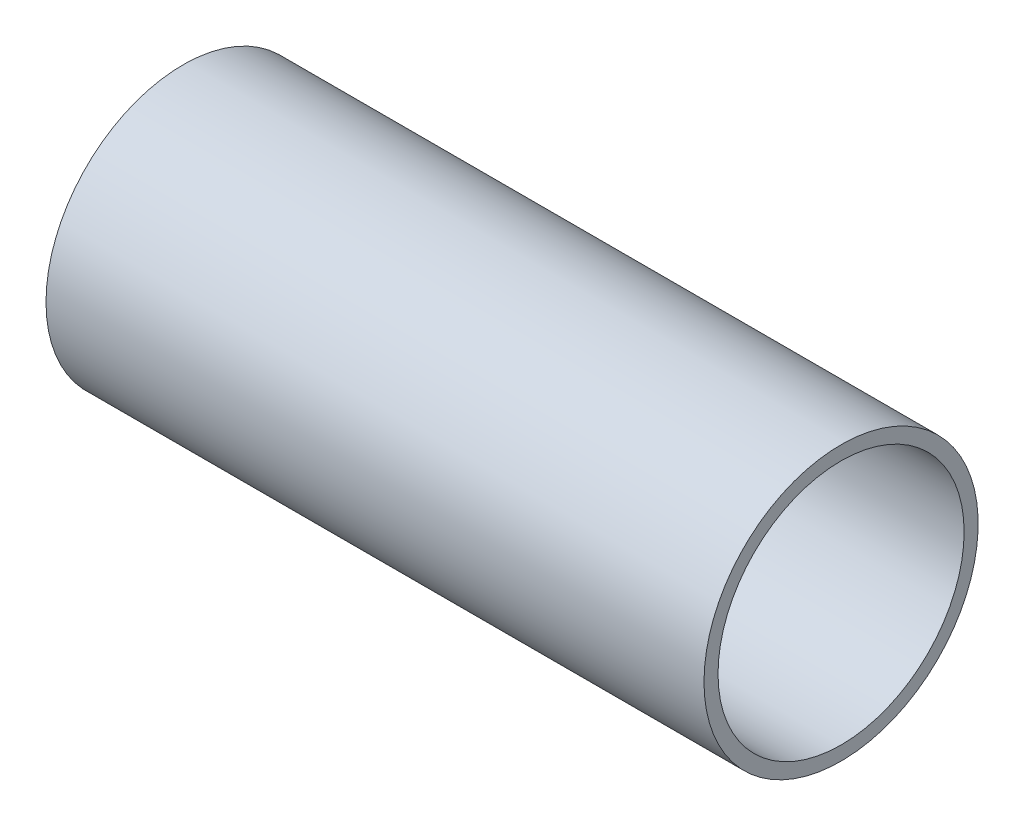
SolidWorks part; units mm, degrees
ref_plane "Front" through (0, 0, 0) normal (0, 0, 1) x (1, 0, 0)
ref_plane "Top" through (0, 0, 0) normal (0, 1, 0) x (1, 0, 0)
ref_plane "Right" through (0, 0, 0) normal (1, 0, 0) x (0, 0, -1)
sketch "Sketch1" plane through (0, 0, 0) normal (1, 0, 0) x (0, 0, -1)
  circle A0 centre (0, 0) radius 14.25
  circle A1 centre (0, 0) radius 15.875
  dimension "D1" = 28.5
  dimension "D2" = 31.75
extrude "Base-Extrude" add sketch "Sketch1" along normal blind 76.2
